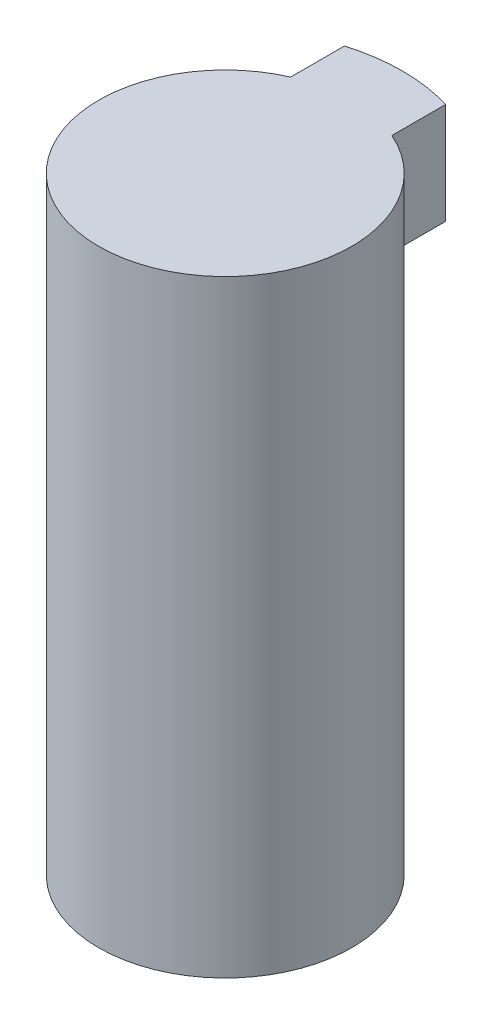
SolidWorks part; units mm, degrees
material "Custom Plastic"
ref_plane "Front Plane" through (0, 0, 0) normal (0, 0, 1) x (1, 0, 0)
ref_plane "Top Plane" through (0, 0, 0) normal (0, 1, 0) x (1, 0, 0)
ref_plane "Right Plane" through (0, 0, 0) normal (1, 0, 0) x (0, 0, -1)
sketch "Sketch1" plane through (0, 0, 0) normal (0, 1, 0) x (1, 0, 0)
  circle A0 centre (0, 0) radius 2.54
  circle A1 centre (0, 0) radius 3.175
  dimension "D1" = 6.35
  dimension "D2" = 5.08
extrude "Boss-Extrude1" add sketch "Sketch1" along normal blind 12.7 contours A1 A0
sketch "Sketch3" plane through (0, 12.7, 0) normal (0, 1, 0) x (1, 0, 0)
  line L0 (0, 3.175) -> (0, 4.445) construction
  line L2 (-1.27, 4.2597) -> (-1.27, 2.9099)
  line L3 (1.27, 4.2597) -> (1.27, 2.9099)
  arc A0 (-1.27, 2.9099) -> (1.27, 2.9099) centre (0, 0) ccw
  circle A1 centre (0, 0) radius 3.175 construction
  arc A2 (1.27, 4.2597) -> (-1.27, 4.2597) centre (0, 0) ccw
  dimension "D2" = 8.89
extrude "Boss-Extrude2" add sketch "Sketch3" along normal blind 2.54
